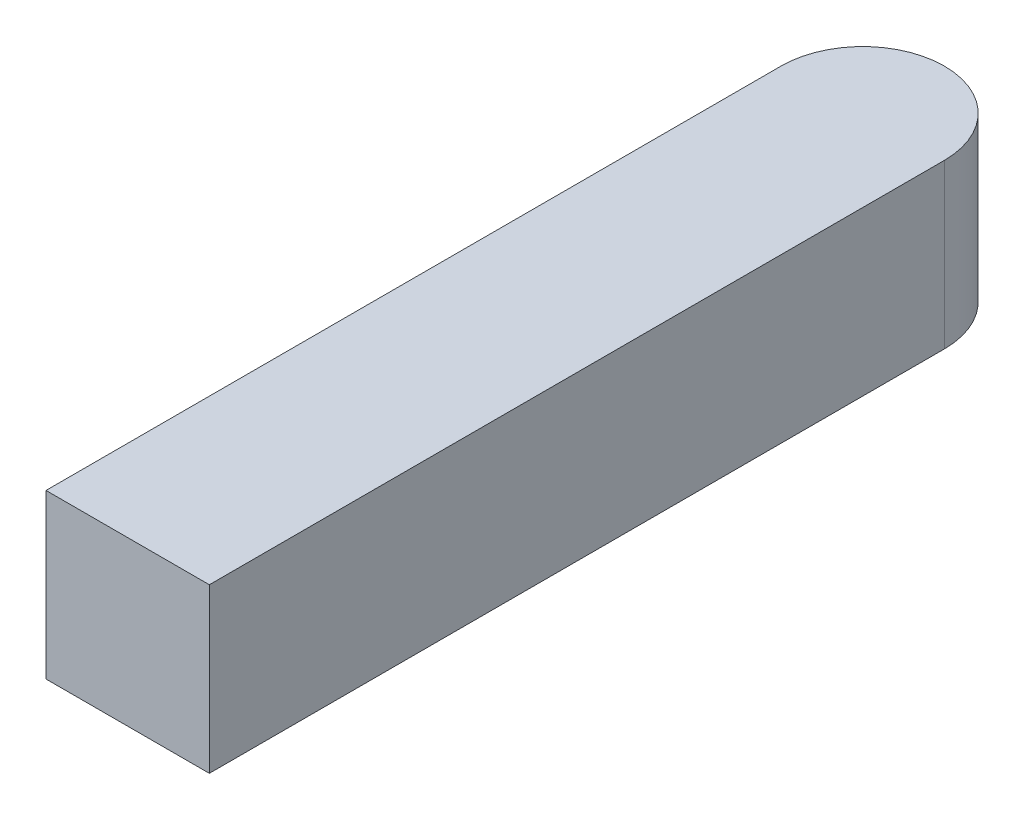
SolidWorks part; units mm, degrees
material "Plain Carbon Steel"
ref_plane "Front Plane" through (0, 0, 0) normal (0, 0, 1) x (1, 0, 0)
ref_plane "Top Plane" through (0, 0, 0) normal (0, 1, 0) x (1, 0, 0)
ref_plane "Right Plane" through (0, 0, 0) normal (1, 0, 0) x (0, 0, -1)
sketch "Sketch2" plane through (0, 0, 0) normal (0, 1, 0) x (1, 0, 0)
  line L0 (0, 0) -> (0, 8140.4332) construction
  line L2 (-1.5, 6.75) -> (-1.5, -6.75)
  line L3 (-1.5, -6.75) -> (1.5, -6.75)
  line L4 (1.5, 6.75) -> (1.5, -6.75)
  line L5 (-1.5, 6.75) -> (1.5, -6.75) construction
  line L6 (-1.5, -6.75) -> (1.5, 6.75) construction
  arc A0 (-1.5, 6.75) -> (1.5, 6.75) centre (0, 6.75) cw
  point P0 (0, 0)
  point P9 (0, 0)
  point P10 (0, 8.25)
  dimension "D1" = 3
  dimension "D2" = 15
extrude "Boss-Extrude1" add sketch "Sketch2" along normal mid plane 3
